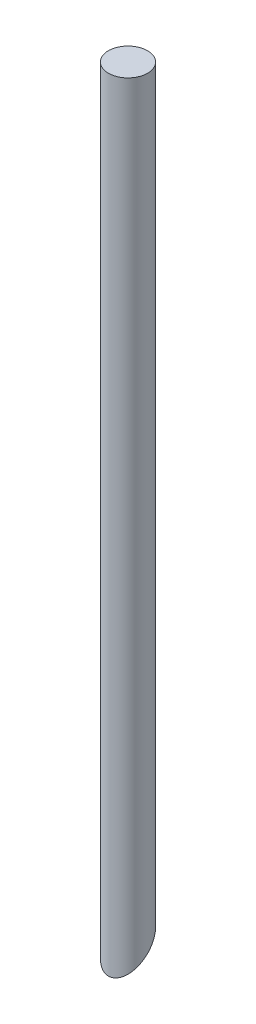
SolidWorks part; units mm, degrees
ref_plane "前视基准面" through (0, 0, 0) normal (0, 0, 1) x (1, 0, 0)
ref_plane "上视基准面" through (0, 0, 0) normal (0, 1, 0) x (1, 0, 0)
ref_plane "右视基准面" through (0, 0, 0) normal (1, 0, 0) x (0, 0, -1)
sketch "草图1" plane through (0, 0, 0) normal (0, 1, 0) x (1, 0, 0)
  circle A0 centre (0, 0) radius 5
  dimension "D1" = 10
extrude "凸台-拉伸1" add sketch "草图1" along normal blind 200
sketch "草图2" plane through (0, 0, 0) normal (1, 0, 0) x (0, 0, -1)
  line L0 (-5, 0) -> (5, 10)
  line L1 (5, 0) -> (5, 200) construction
  line L2 (-5, 0) -> (5, 0) construction
  line L3 (5, 10) -> (5, 0)
  line L4 (5, 0) -> (-5, 0)
  dimension "D1" = 45
extrude "切除-拉伸1" cut sketch "草图2" against normal through all both and the other way through all
